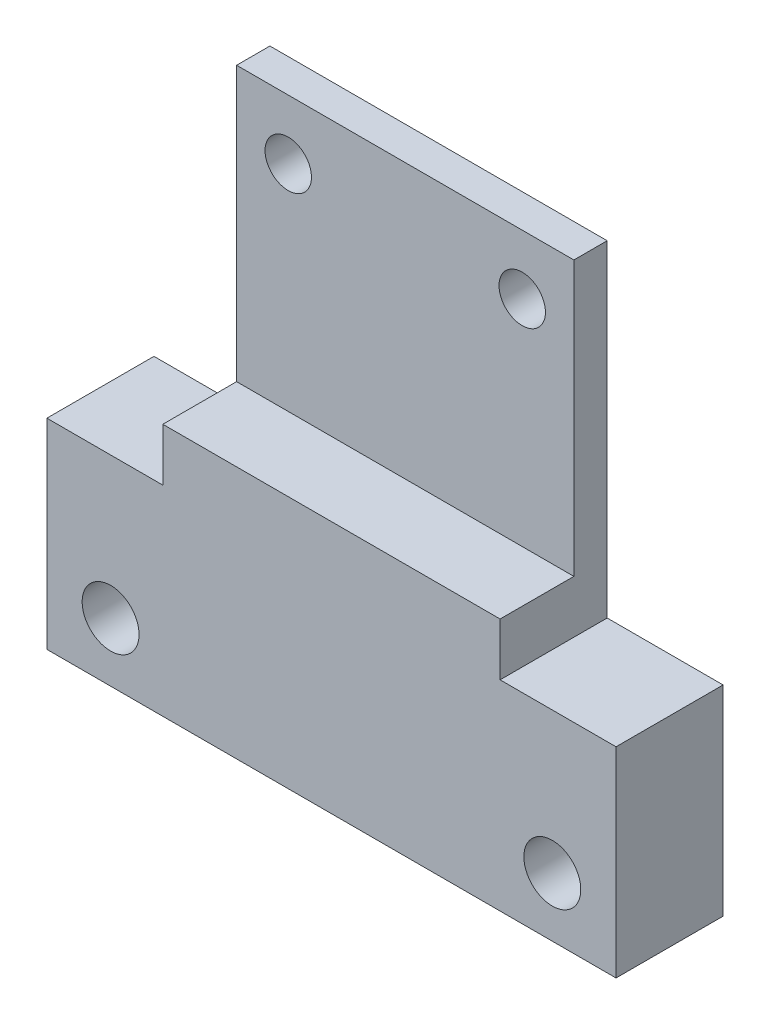
SolidWorks part; units mm, degrees
ref_plane "Front Plane" through (0, 0, 0) normal (0, 0, 1) x (1, 0, 0)
ref_plane "Top Plane" through (0, 0, 0) normal (0, 1, 0) x (1, 0, 0)
ref_plane "Right Plane" through (0, 0, 0) normal (1, 0, 0) x (0, 0, -1)
sketch "Sketch1" plane through (0, 0, 0) normal (0, 0, 1) x (1, 0, 0)
  line L0 (0, 9.5) -> (5.5, 9.5)
  line L1 (0, 0) -> (27, 0)
  line L2 (0, 0) -> (0, 9.5)
  line L3 (5.5, 25) -> (21.5, 25)
  line L4 (27, 0) -> (27, 9.5)
  line L5 (13.5, 25) -> (13.5, 0) construction
  line L6 (5.5, 25) -> (5.5, 9.5)
  line L7 (21.5, 25) -> (21.5, 9.5)
  line L8 (21.5, 9.5) -> (27, 9.5)
  point P2 (-45.3968, 35.1974)
  point P3 (-18.8838, 21.1834)
  point P13 (0, 0)
  point P14 (-36.9018, 32.8707)
  dimension "D1" = 27
  dimension "D2" = 15.5
  dimension "D3" = 9.5
  dimension "D4" = 8
  dimension "D5" = 8
extrude "Boss-Extrude1" add sketch "Sketch1" along normal blind 5.08
sketch "Sketch2" plane through (0, 0, 5.08) normal (0, 0, 1) x (1, 0, 0)
  line L0 (21.5, 25) -> (5.5, 25) construction
  line L1 (5.5, 25) -> (21.5, 25)
  line L2 (5.5, 25) -> (5.5, 12)
  line L3 (5.5, 12) -> (21.5, 12)
  line L4 (21.5, 25) -> (21.5, 12)
  line L5 (5.5, 25) -> (5.5, 9.5) construction
  line L6 (21.5, 9.5) -> (21.5, 25) construction
  dimension "D1" = 13
extrude "Cut-Extrude1" cut sketch "Sketch2" against normal blind 3.5
sketch "Sketch3" plane through (0, 0, 0) normal (0, 0, -1) x (-1, 0, 0)
  line L0 (-13.5, 25) -> (-13.5, 0) construction
  line L1 (-21.5, 25) -> (-5.5, 25) construction
  line L2 (0, 0) -> (-27, 0) construction
  line L3 (-27, 0) -> (-27, 9.5) construction
  line L4 (0, 9.5) -> (0, 0) construction
  circle A0 centre (-23.9775, 2.794) radius 2
  circle A1 centre (-3.0225, 2.794) radius 2
  dimension "D1" = 4
  dimension "D2" = 2.794
  dimension "D3" = 2.794
  dimension "D4" = 3.0225
  dimension "D5" = 3.0225
extrude "Cut-Extrude2" cut sketch "Sketch3" against normal blind 3
sketch "Sketch4" plane through (0, 0, 0) normal (0, 0, -1) x (-1, 0, 0)
  line L0 (-13.5, 25) -> (-13.5, 0) construction
  line L1 (-21.5, 25) -> (-5.5, 25) construction
  line L2 (0, 0) -> (-27, 0) construction
  line L3 (-21.5, 9.5) -> (-21.5, 25) construction
  line L4 (-5.5, 25) -> (-5.5, 9.5) construction
  circle A0 centre (-19.0499, 22.1742) radius 1.1
  circle A1 centre (-7.9501, 22.1742) radius 1.1
  dimension "D1" = 2.2
  dimension "D2" = 2.8258
  dimension "D3" = 2.8258
  dimension "D4" = 2.4501
  dimension "D5" = 2.4501
extrude "Cut-Extrude3" cut sketch "Sketch4" against normal blind 21
sketch "Sketch5" plane through (0, 0, 3) normal (0, 0, -1) x (-1, 0, 0)
  circle A0 centre (-23.9775, 2.794) radius 1.35
  circle A1 centre (-3.0225, 2.794) radius 1.35
extrude "Cut-Extrude4" cut sketch "Sketch5" against normal blind 21
